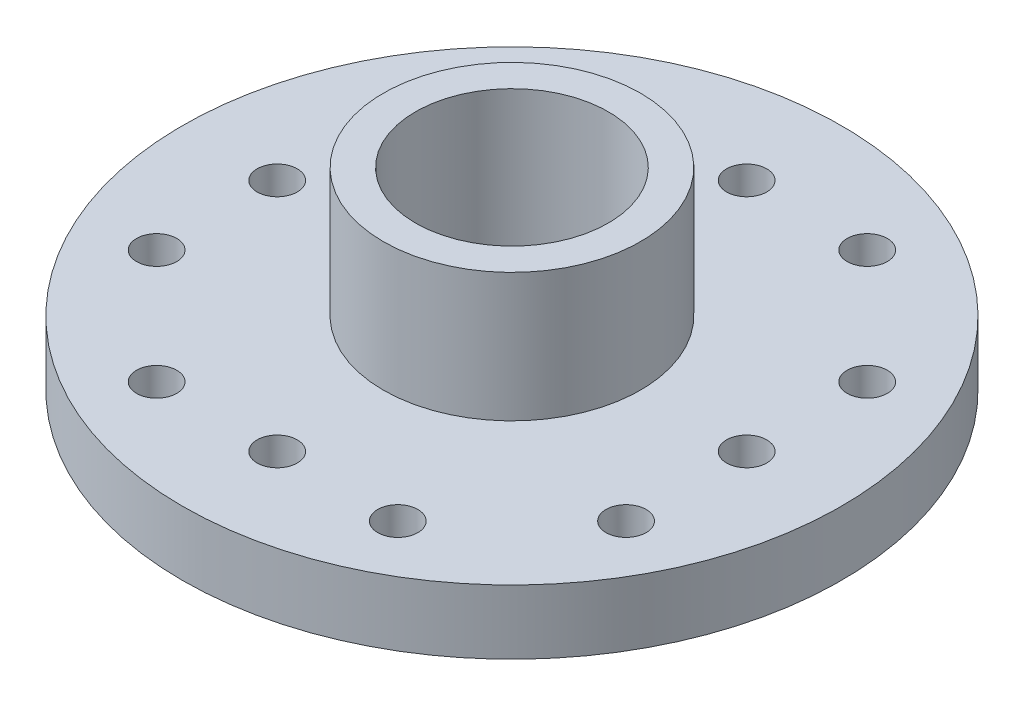
SolidWorks part; units mm, degrees
ref_plane "Front" through (0, 0, 0) normal (0, 0, 1) x (1, 0, 0)
ref_plane "Top" through (0, 0, 0) normal (0, 1, 0) x (1, 0, 0)
ref_plane "Right" through (0, 0, 0) normal (1, 0, 0) x (0, 0, -1)
sketch "Sketch1" plane through (0, 0, 0) normal (0, 1, 0) x (1, 0, 0)
  circle A0 centre (0, 0) radius 3
  circle A1 centre (0, 0) radius 10.25
  dimension "D1" = 6
  dimension "D2" = 20.5
extrude "Boss-Extrude1" add sketch "Sketch1" along normal blind 2
sketch "Çizim1" plane through (0, 2, 0) normal (0, 1, 0) x (1, 0, 0)
  circle A0 centre (0, 0) radius 4
  circle A1 centre (0, 0) radius 3
  dimension "D1" = 8
extrude "Yükseklik-Ekstrüzyon1" add sketch "Çizim1" along normal blind 4
sketch "Çizim2" plane through (0, 2, 0) normal (0, 1, 0) x (1, 0, 0)
  line L0 (0, 0) -> (10.25, 0) construction
  circle A0 centre (0, 0) radius 10.25 construction
  circle A1 centre (7.3, 0) radius 0.625
  circle A2 centre (7.3, 3.75) radius 0.625
  circle A3 centre (7.3, -3.75) radius 0.625
  dimension "D1" = 1.25
  dimension "D2" = 7.3
  dimension "D3" = 3.75
extrude "Kes-Ekstrüzyon1" cut sketch "Çizim2" against normal up to next
pattern_circular "Dairesel Çoğaltma1" count 4 over 360 about axis through (0, 0, 0) along (0, 1, 0) of "Kes-Ekstrüzyon1"
